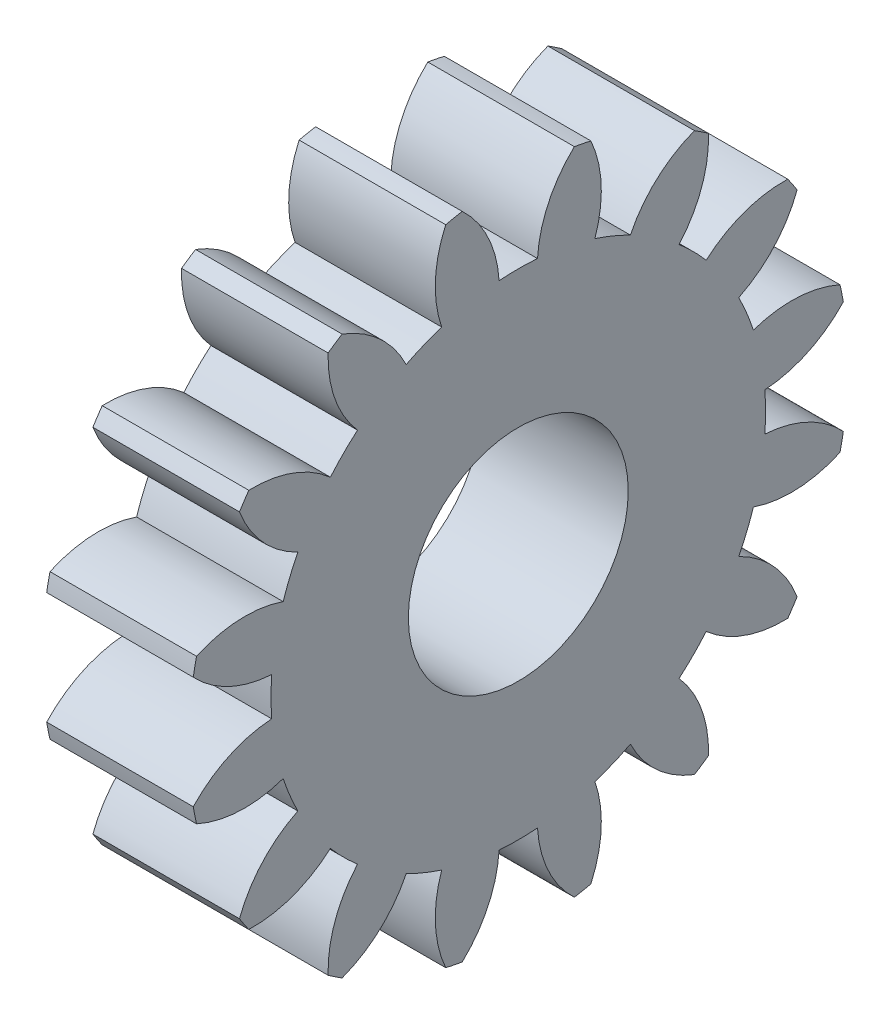
SolidWorks part; units mm, degrees
material "PP Homopolymer"
ref_plane "Plane1" through (0, 0, 0) normal (0, 0, 1) x (1, 0, 0)
ref_plane "Plane2" through (0, 0, 0) normal (0, 1, 0) x (1, 0, 0)
ref_plane "Plane3" through (0, 0, 0) normal (1, 0, 0) x (0, 0, -1)
sketch "HoldingSke" plane through (0, 0, 0) normal (0, 1, 0) x (1, 0, 0)
  line L0 (0, 0) -> (1.9225, -0.5513)
  line L1 (-15, 0) -> (100, 0) construction
  line L2 (0, 0) -> (-2.1039, 2.3779)
  line L3 (0, 0) -> (-11.863, 4.5341)
  line L4 (0, 0) -> (8.3015, 2.3804)
  line L5 (0, 0) -> (-46.8476, -17.4728)
  line L6 (0, 0) -> (-1.6579, -1.1186)
  line L7 (-2.1039, 2.3779) -> (8.6586, 51.2059)
  line L8 (-76.2, 54.61) -> (-75.7, 54.61)
  line L9 (-71.009, 38.7566) -> (-53.1078, 45.2721)
  line L10 (-76.2, 71.12) -> (104.1128, 71.12)
  line L11 (0, 0) -> (-2, 0)
  line L12 (-76.2, 101.6) -> (-76.181, 101.6)
  line L13 (24.9733, 27.94) -> (52.9518, 28.4284)
  line L14 (24.9733, 27.94) -> (24.9743, 27.94)
  line L15 (24.9733, 27.94) -> (100.4006, 29.5858)
  line L16 (-63.627, -0.5) -> (-12.827, -0.5)
  circle A0 centre (0, 0) radius 1.5
  circle A1 centre (0, 0) radius 3.374
  circle A2 centre (0, 0) radius 37.5
  circle A3 centre (0, 0) radius 1.5
  dimension "MHD" = 6.748
  dimension "Hub_dia" = 75
  dimension "Bore" = 3
  dimension "MBD" = 3
  dimension "Num_teeth" = 16
  dimension "Pitch_radius" = 180.3128
  dimension "Pitch" = 2
  dimension "Width" = 2
  dimension "Overall_len" = 50
  dimension "Show_teeth" = 16
  dimension "Thickness" = 2
  dimension "OAL" = 50.0001
  dimension "T_dim" = 0.5
  dimension "Ap" = 20
  dimension "H" = 19.05
  dimension "Backlash" = 0.019
  dimension "Addendum_fac" = 1
  dimension "Dedendum_fac" = 1.25
  dimension "Clearance_fac" = 0.25
  dimension "Dedendum_add" = 0.001
  dimension "Module" = 0.5
sketch "BasProSke" plane through (0, 0, 0) normal (0, 1, 0) x (1, 0, 0)
  line L0 (-10, 0) -> (60, 0) construction
  line L1 (0, 0) -> (0, 4.5)
  line L2 (0, 0) -> (2, 0)
  line L3 (2, 0) -> (2, 4.5)
  line L4 (2, 4.5) -> (0, 4.5)
  dimension "Diameter" = 9
  dimension "Thickness" = 2
revolve "Base-Revolve" add sketch "BasProSke" angle 360 about L0
sketch "TooCutSke" plane through (0, 0, 0) normal (1, 0, 0) x (0, 0, -1)
  line L1 (0, 0) -> (0, 107) construction
  line L2 (0, 0) -> (-0.4253, 3.9773) construction
  line L3 (0, 0) -> (-1.5544, 7.8146) construction
  line L4 (-0.4253, 3.9773) -> (-0.7772, 3.9073) construction
  arc A0 (0.2619, 3.3638) -> (-0.2619, 3.3638) centre (0, 0) ccw
  arc A1 (0.7886, 4.4562) -> (-0.7886, 4.4562) centre (0, 0) ccw
  circle A2 centre (0, 0) radius 4 construction
  circle A3 centre (0, 0) radius 3.7588 construction
  arc A4 (-0.2619, 3.3638) -> (-0.7886, 4.4562) centre (-1.8589, 3.2669) ccw
  arc A5 (0.7886, 4.4562) -> (0.2619, 3.3638) centre (1.8589, 3.2669) ccw
  dimension "Root_dia" = 6.748
  dimension "Overcut_dia" = 9.0508
  dimension "Pitch_dia" = 8
  dimension "Base_dia" = 7.5175
  dimension "Flank_rad" = 1.6
  dimension "Half_ang" = 11.25
  dimension "Half_CT" = 0.3588
extrude "ToothCut" cut sketch "TooCutSke" along normal through all
fillet "Breaks" [suppressed] radius 0.01
fillet "RootFillets" [suppressed] radius 0.126
pattern_circular "TeethCuts" count 16 every 22.5 about axis through (-10, 0, 0) along (1, 0, 0) of "ToothCut", "RootFillets", "Breaks"
sketch "HubNeaOneSke" plane through (0, 0, 0) normal (-1, 0, 0) x (0, 0, 1)
  circle A0 centre (0, 0) radius 3.374
  dimension "Diameter" = 6.748
extrude "HubNearOne" [suppressed] add sketch "HubNeaOneSke" along normal blind 48.0001
sketch "HubNeaBotSke" plane through (0, 0, 0) normal (-1, 0, 0) x (0, 0, 1)
  circle A0 centre (0, 0) radius 3.374
  dimension "Diameter" = 6.748
extrude "HubNearBoth" [suppressed] add sketch "HubNeaBotSke" along normal blind 24
ref_plane "FarPln" through (2, 0, 0) normal (1, 0, 0) x (0, 0, -1)
sketch "HubFarSke" plane through (2, 0, 0) normal (1, 0, 0) x (0, 0, -1)
  circle A0 centre (0, 0) radius 3.374
  dimension "Diameter" = 6.748
extrude "HubFar" [suppressed] add sketch "HubFarSke" along normal blind 24
sketch "BorSke" plane through (0, 0, 0) normal (1, 0, 0) x (0, 0, -1)
  circle A0 centre (0, 0) radius 1.5
  dimension "Diameter" = 3
extrude "Bore" cut sketch "BorSke" along normal mid plane 100.0001
sketch "KeySke" plane through (0, 0, 0) normal (1, 0, 0) x (0, 0, -1)
  line L0 (-0.6, 0) -> (-0.6, 2)
  line L1 (-0.6, 2) -> (0.6, 2)
  line L2 (0.6, 2) -> (0.6, 0)
  line L3 (0, 0) -> (0, 34) construction
  line L4 (-0.6, 0) -> (0.6, 0)
  dimension "Offset" = 2
  dimension "Width" = 1.2
extrude "Keyway" [suppressed] cut sketch "KeySke" along normal mid plane 100.0001
pattern_circular "Keyway2" [suppressed] count 2 every 90 about axis through (-10, 0, 0) along (1, 0, 0)
equation "' \"Module@HoldingSke\" = 6.35"
equation "' \"Num_teeth@HoldingSke\" = 12"
equation "' \"Ap@HoldingSke\" =  20"
equation "' \"Width@HoldingSke\" = 0.5 * 25.4"
equation "' \"Hub_dia@HoldingSke\"= 1 * 25.4"
equation "' \"Overall_len@HoldingSke\" = 1.0 * 25.4"
equation "' \"Bore@HoldingSke\" = 0.75 * 25.4"
equation "' \"T_dim@HoldingSke\" = 0.1 * 25.4"
equation "' \"Width@KeySke\" = 0.25 * 25.4"
equation "' \"Show_teeth@HoldingSke\" = 13"
equation "' \"Backlash@HoldingSke\" = 0.009 * 25.4"
equation "' \"Addendum_fac@HoldingSke\" = 1.0"
equation "' \"Dedendum_fac@HoldingSke\" = 1.25"
equation "' \"Dedendum_add@HoldingSke\" = 0.00005 * 25.4"
equation "' \"Clearance_fac@HoldingSke\" = 0.25"
equation "\"Pitch@HoldingSke\" = 1 / \"Module@HoldingSke\""
equation "\"Overcut_dia@TooCutSke\" = (\"Num_teeth@HoldingSke\" + 2 * \"Addendum_fac@HoldingSke\") / \"Pitch@HoldingSke\" + 0.002 * 25.4"
equation "\"Pitch_dia@TooCutSke\" = \"Num_teeth@HoldingSke\" / \"Pitch@HoldingSke\""
equation "\"Base_dia@TooCutSke\" = \"Num_teeth@HoldingSke\" / \"Pitch@HoldingSke\" * cos((\"Ap@HoldingSke\"  * 3.14159265 / 180))"
equation "\"Root_dia@TooCutSke\" = (\"Num_teeth@HoldingSke\" + 2) / \"Pitch@HoldingSke\" - 2 * (\"Addendum_fac@HoldingSke\" + \"Dedendum_fac@HoldingSke\") / \"Pitch@HoldingSke\" - \"Dedendum_add@HoldingSke\" * 2"
equation "\"Half_ang@TooCutSke\" = 180 / \"Num_teeth@HoldingSke\""
equation "\"Half_CT@TooCutSke\" = \"Num_teeth@HoldingSke\" / \"Pitch@HoldingSke\" * sin((3.14159265 / 2 / \"Num_teeth@HoldingSke\")) / 2 - 7 * \"Backlash@HoldingSke\" / 4"
equation "\"Flank_rad@TooCutSke\" = \"Num_teeth@HoldingSke\" / \"Pitch@HoldingSke\" / 5"
equation "\"Radius@RootFillets\" = \"Clearance_fac@HoldingSke\" / \"Pitch@HoldingSke\" + \"Dedendum_add@HoldingSke\""
equation "\"Break_rad@Breaks\" = 0.02 / \"Pitch@HoldingSke\""
equation "\"Thickness@HoldingSke\" = \"Width@HoldingSke\""
equation "\"OAL@HoldingSke\" = \"Thickness@HoldingSke\""
equation "\"MHD@HoldingSke\" = (\"Num_teeth@HoldingSke\" + 2) / \"Pitch@HoldingSke\" - 2 * (\"Addendum_fac@HoldingSke\" + \"Dedendum_fac@HoldingSke\")  / \"Pitch@HoldingSke\" - \"Dedendum_add@HoldingSke\" * 2"
equation "\"MBD@HoldingSke\" = (\"Num_teeth@HoldingSke\" + 2) / \"Pitch@HoldingSke\" - 2 * (\"Addendum_fac@HoldingSke\" + \"Dedendum_fac@HoldingSke\")  / \"Pitch@HoldingSke\" - \"Dedendum_add@HoldingSke\" * 2 - 0.002 * 25.4"
equation "\"MHD@HoldingSke\" = ((sgn( \"MHD@HoldingSke\" - \"Hub_dia@HoldingSke\" )-1)*( \"MHD@HoldingSke\" - \"Hub_dia@HoldingSke\" ))/-2+ \"Hub_dia@HoldingSke\""
equation "\"MBD@HoldingSke\" = ((sgn( \"MBD@HoldingSke\" - \"Bore@HoldingSke\" )-1)*( \"MBD@HoldingSke\" - \"Bore@HoldingSke\" ))/-2+ \"Bore@HoldingSke\""
equation "\"OAL@HoldingSke\" = ((sgn( \"OAL@HoldingSke\" - \"Overall_len@HoldingSke\" )+1)*( \"OAL@HoldingSke\" - \"Overall_len@HoldingSke\" ))/2 + \"Overall_len@HoldingSke\" + 0.000002 * 25.4"
equation "\"Num_teeth@TeethCuts\" = int( \"Show_teeth@HoldingSke\" ) + 1"
equation "\"Num_teeth@TeethCuts\" = ((sgn( \"Num_teeth@TeethCuts\" - \"Num_teeth@HoldingSke\" )-1)*( \"Num_teeth@TeethCuts\" - \"Num_teeth@HoldingSke\" ))/-2+ \"Num_teeth@HoldingSke\""
equation "\"Num_teeth@TeethCuts\" = ((sgn( \"Num_teeth@TeethCuts\" - 2.0)+1)*( \"Num_teeth@TeethCuts\" - 2.0))/2 +2.0"
equation "\"Angle@TeethCuts\" = 360.0 / \"Num_teeth@HoldingSke\""
equation "\"Diameter@BasProSke\" = (\"Num_teeth@HoldingSke\" + 2 * \"Addendum_fac@HoldingSke\") / \"Pitch@HoldingSke\""
equation "\"Thickness@BasProSke\"  = \"Thickness@HoldingSke\""
equation "' \"Fillet_rad@BasProSke\" =  \"Thickness@HoldingSke\" * 0.05"
equation "\"MHD@HoldingSke\" = ((sgn( \"MHD@HoldingSke\" - \"Root_dia@TooCutSke\" )-1)*( \"MHD@HoldingSke\" - \"Root_dia@TooCutSke\" ))/-2+ \"Root_dia@TooCutSke\""
equation "\"Diameter@HubNeaOneSke\" = \"MHD@HoldingSke\""
equation "\"Length@HubNearOne\" = \"OAL@HoldingSke\" - \"Thickness@BasProSke\""
equation "\"Diameter@HubNeaBotSke\" = \"MHD@HoldingSke\""
equation "\"Length@HubNearBoth\" = ( \"OAL@HoldingSke\" - \"Thickness@BasProSke\" ) / 2.0"
equation "\"Thickness@FarPln\" = \"Thickness@BasProSke\""
equation "\"Diameter@HubFarSke\" = \"MHD@HoldingSke\""
equation "\"Length@HubFar\" = ( \"OAL@HoldingSke\" - \"Thickness@BasProSke\" ) / 2.0"
equation "\"Diameter@BorSke\" = \"MBD@HoldingSke\""
equation "\"D1@Bore\" = \"OAL@HoldingSke\" * 2.0"
equation "\"D1@Keyway\" = \"OAL@HoldingSke\" * 2.0"
equation "\"Offset@KeySke\" = \"T_dim@HoldingSke\" + \"MBD@HoldingSke\" / 2.0"
